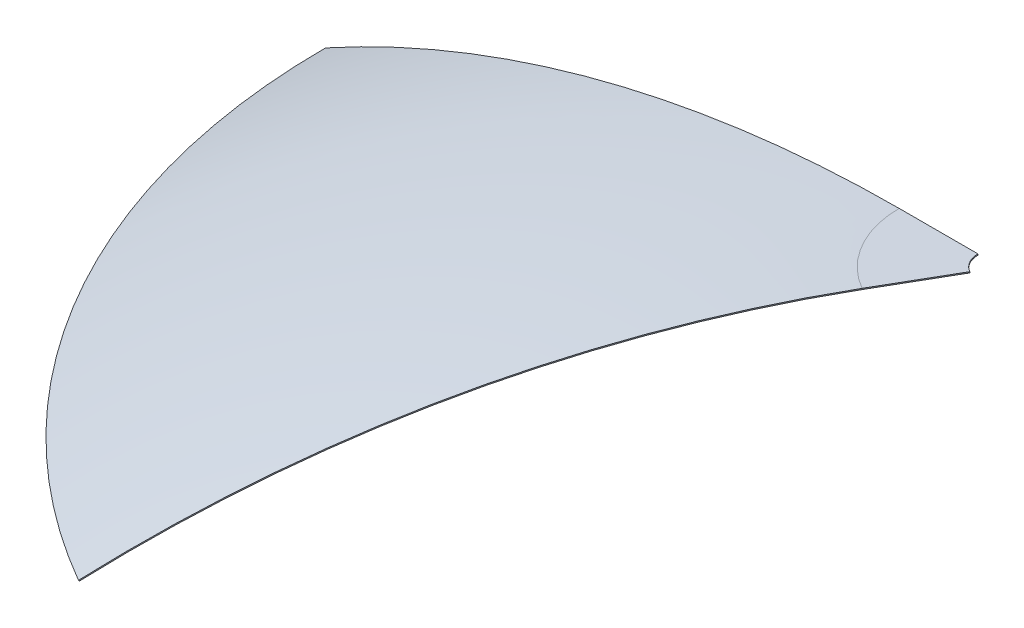
SolidWorks part; units mm, degrees
ref_plane "Front Plane" through (0, 0, 0) normal (0, 0, 1) x (1, 0, 0)
ref_plane "Top Plane" through (0, 0, 0) normal (0, 1, 0) x (1, 0, 0)
ref_plane "Right Plane" through (0, 0, 0) normal (1, 0, 0) x (0, 0, -1)
sketch "Sketch1" plane through (0, 0, 0) normal (0, 0, 1) x (1, 0, 0)
  line L0 (45, 1.9367) -> (-45, 1.9367) construction
  line L1 (45, 1.9367) -> (-45, 1.9367) construction
  line L2 (10, 1.9367) -> (-10, 1.9367) construction
  line L3 (10, 1.9367) -> (-10, 1.9367) construction
  line L4 (-45, 1.9367) -> (-10, 1.9367)
  line L6 (-45.0004, 2.4367) -> (-10, 2.4367)
  line L7 (-10, 2.4367) -> (-10, 1.9367)
  line L8 (-299.7402, -63.211) -> (-299.4992, -63.6491)
  line L9 (0, -998.5) -> (0, 49001.5) construction
  arc A1 (-46.1132, 1.9338) -> (-299.4992, -63.6491) centre (-44.2035, -527.7266) ccw
  arc A2 (-45, 1.9367) -> (-46.1132, 1.9338) centre (-44.2035, -527.7266) ccw
  arc A3 (-46.115, 2.4338) -> (-299.7402, -63.211) centre (-44.2035, -527.7266) ccw
  arc A4 (-45.0004, 2.4367) -> (-46.115, 2.4338) centre (-44.2035, -527.7266) ccw
  point P17 (0, 1.9367)
  dimension "D1" = 0.5
  dimension "D2" = 1.1132
  dimension "D3" = 264.4748
  dimension "D4" = 1.1132
  dimension "D5" = 35
revolve "Revolve1" add sketch "Sketch1" angle 60 about L9
sketch "Sketch3" plane through (0, 2.4367, 0) normal (0, 1, 0) x (1, 0, 0)
  line L0 (-10, 0) -> (-5, -8.6603)
  arc A0 (-10, 0) -> (-5, -8.6603) centre (0, 0) ccw construction
  arc A1 (-10, 0) -> (-5, -8.6603) centre (0, 0) ccw
extrude "Boss-Extrude1" [suppressed] add sketch "Sketch3" against normal up to surface (0.5 mm away)
sketch "Sketch4" plane through (0, 0, 0) normal (0, 1, 0) x (1, 0, 0)
  circle A0 centre (0, 0) radius 50.25
  dimension "D1" = 100.5
extrude "Cut-Extrude3" [suppressed] cut sketch "Sketch4" along normal blind 10
